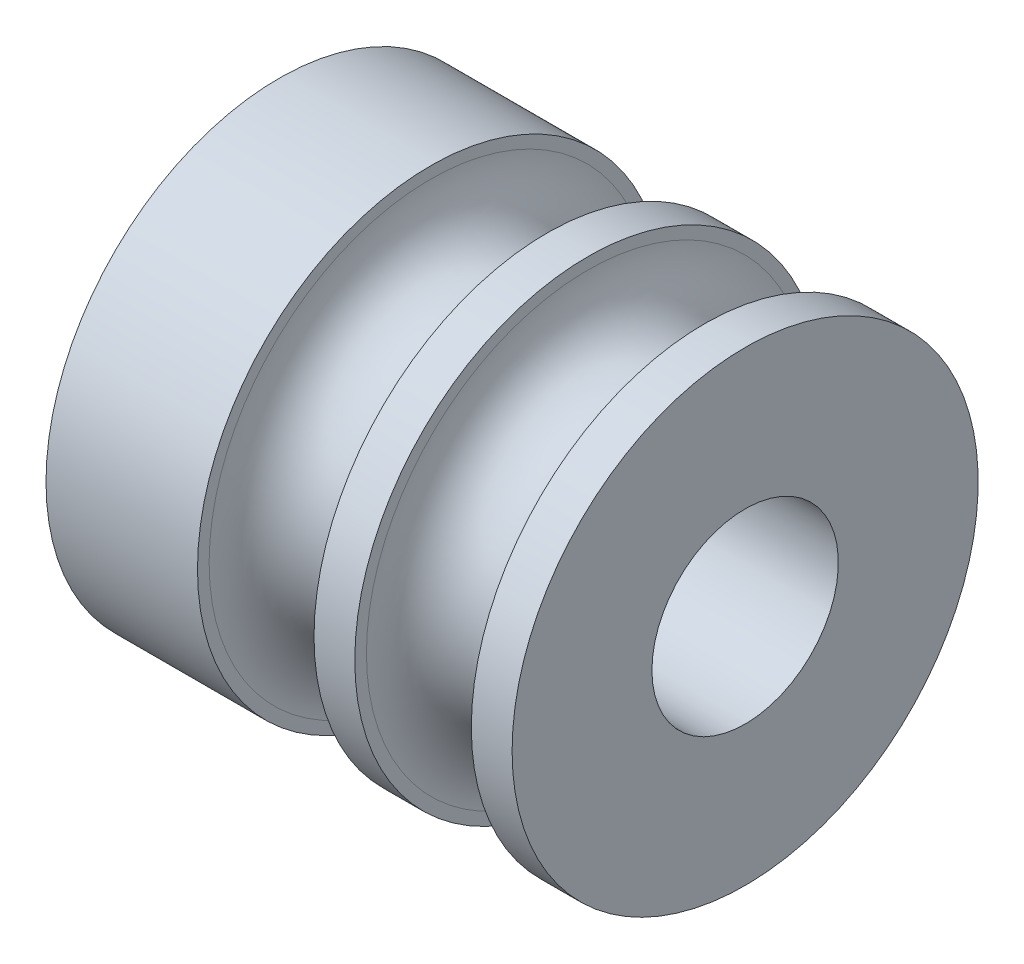
SolidWorks part; units mm, degrees
ref_plane "Front Plane" through (0, 0, 0) normal (0, 0, 1) x (1, 0, 0)
ref_plane "Top Plane" through (0, 0, 0) normal (0, 1, 0) x (1, 0, 0)
ref_plane "Right Plane" through (0, 0, 0) normal (1, 0, 0) x (0, 0, -1)
sketch "Sketch1" plane through (0, 0, 0) normal (0, 1, 0) x (1, 0, 0)
  line L0 (-17.2228, 0) -> (20.2228, 0) construction
  line L1 (-3.5, 10) -> (-3.5, 9.5)
  line L2 (-10, 10) -> (-3.5, 10)
  line L3 (-10, 10) -> (-10, 4)
  line L5 (10, 10) -> (10, 4)
  line L6 (1.5, 10) -> (1.5, 9.5)
  line L7 (3.25, 10) -> (3.25, 9.5)
  line L8 (8.25, 10) -> (8.25, 9.5)
  line L9 (5.75, 9.5) -> (-1, 9.5) construction
  line L10 (1.5, 10) -> (3.25, 10)
  line L11 (8.25, 10) -> (10, 10)
  line L12 (-10, 4) -> (10, 4)
  arc A1 (3.25, 9.5) -> (8.25, 9.5) centre (5.75, 9.5) ccw
  arc A2 (-3.5, 9.5) -> (1.5, 9.5) centre (-1, 9.5) ccw
  point P3 (0, 0)
  dimension "D7" = 4
  dimension "D8" = 4.25
  dimension "D1" = 20
  dimension "D2" = 10
  dimension "D3" = 6.5
  dimension "D4" = 5
  dimension "D5" = 5
  dimension "D6" = 1.75
  dimension "D9" = 9.5
  dimension "D10" = 10
revolve "Revolve1" add sketch "Sketch1" angle 360 about L0
